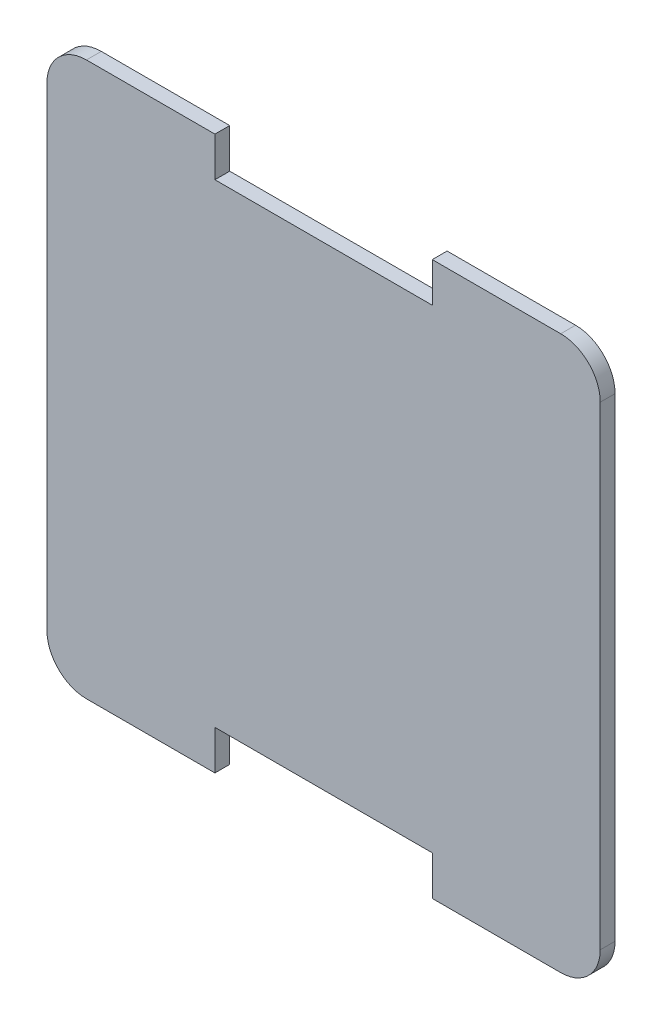
SolidWorks part; units mm, degrees
ref_plane "Front Plane" through (0, 0, 0) normal (0, 0, 1) x (1, 0, 0)
ref_plane "Top Plane" through (0, 0, 0) normal (0, 1, 0) x (1, 0, 0)
ref_plane "Right Plane" through (0, 0, 0) normal (1, 0, 0) x (0, 0, -1)
sketch "Sketch1" plane through (0, 0, 0) normal (0, 0, 1) x (1, 0, 0)
  line L1 (25.4, 0) -> (330.2, 0)
  line L2 (0, 25.4) -> (0, 330.2)
  line L3 (25.4, 355.6) -> (330.2, 355.6)
  line L4 (355.6, 25.4) -> (355.6, 330.2)
  arc A0 (25.4, 0) -> (0, 25.4) centre (25.4, 25.4) cw
  arc A1 (330.2, 0) -> (355.6, 25.4) centre (330.2, 25.4) ccw
  arc A2 (330.2, 355.6) -> (355.6, 330.2) centre (330.2, 330.2) cw
  arc A3 (0, 330.2) -> (25.4, 355.6) centre (25.4, 330.2) cw
  point P7 (0, 0)
  point P10 (355.6, 0)
  point P15 (0, 355.6)
  dimension "D3" = 25.4
  dimension "D1" = 355.6
  dimension "D2" = 355.6
extrude "Boss-Extrude1" add sketch "Sketch1" along normal blind 9.525
sketch "Sketch2" plane through (0, 0, 0) normal (0, 0, -1) x (-1, 0, 0)
  line L0 (-330.2, 355.6) -> (-25.4, 355.6) construction
  line L1 (-247.65, 355.6) -> (-107.95, 355.6)
  line L2 (-247.65, 355.6) -> (-247.65, 330.2)
  line L3 (-247.65, 330.2) -> (-107.95, 330.2)
  line L4 (-107.95, 355.6) -> (-107.95, 330.2)
  line L5 (-247.65, 25.4) -> (-107.95, 25.4)
  line L6 (-247.65, 25.4) -> (-247.65, 0)
  line L7 (-247.65, 0) -> (-107.95, 0)
  line L8 (-107.95, 25.4) -> (-107.95, 0)
  line L9 (-25.4, 0) -> (-330.2, 0) construction
  line L10 (-355.6, 25.4) -> (-355.6, 330.2) construction
  dimension "D1" = 25.4
  dimension "D2" = 25.4
  dimension "D3" = 139.7
  dimension "D4" = 107.95
extrude "Cut-Extrude1" cut sketch "Sketch2" against normal through all
